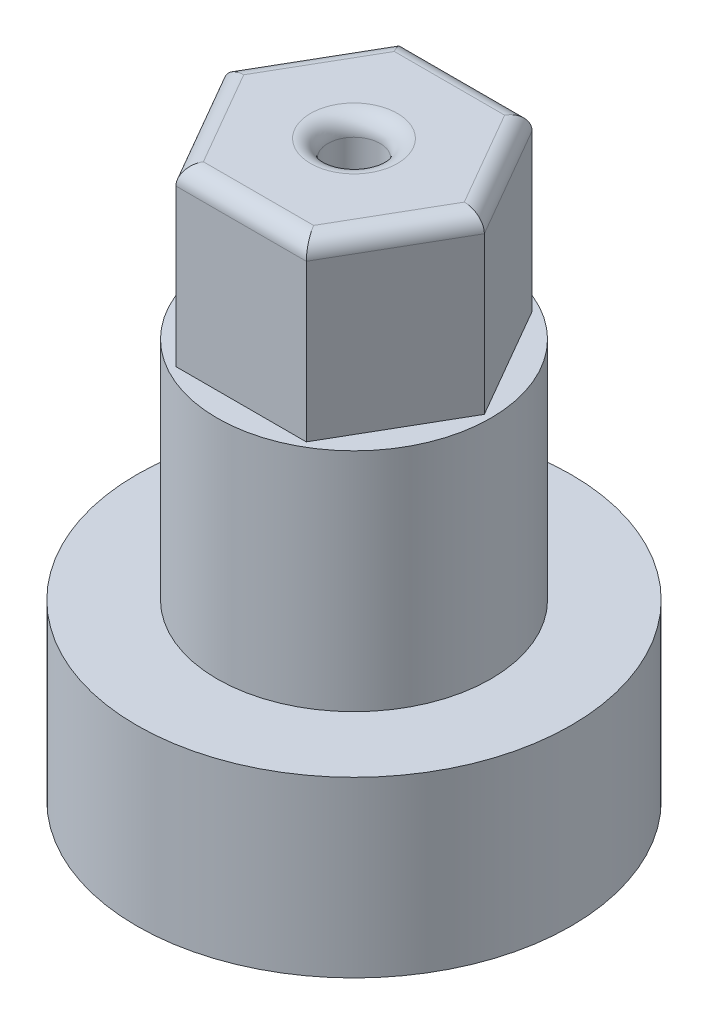
SolidWorks part; units mm, degrees
ref_plane "Alzado" through (0, 0, 0) normal (0, 0, 1) x (1, 0, 0)
ref_plane "Planta" through (0, 0, 0) normal (0, 1, 0) x (1, 0, 0)
ref_plane "Vista lateral" through (0, 0, 0) normal (1, 0, 0) x (0, 0, -1)
sketch "Croquis1" plane through (0, 0, 0) normal (0, 1, 0) x (1, 0, 0)
  line L0 (-12.5, 0) -> (12.5, 0) construction
  circle A0 centre (0, 0) radius 12.5
  circle A1 centre (7, 0) radius 0.75
  circle A2 centre (0, -7) radius 0.75
  circle A3 centre (-7, 0) radius 0.75
  circle A4 centre (0, 7) radius 0.75
  point P16 (0, 0)
  dimension "D1" = 25
  dimension "D2" = 1.5
  dimension "D3" = 7
  dimension "D4" = 4
extrude "Saliente-Extruir1" add sketch "Croquis1" along normal blind 10
sketch "Croquis2" plane through (0, 10, 0) normal (0, 1, 0) x (1, 0, 0)
  circle A0 centre (0, 0) radius 7.875
  dimension "D1" = 15.75
extrude "Saliente-Extruir2" add sketch "Croquis2" along normal blind 13
sketch "Croquis5" plane through (0, 10, 0) normal (0, 1, 0) x (1, 0, 0)
  circle A0 centre (0, 0) radius 12.5
sketch "Croquis3" plane through (0, 23, 0) normal (0, 1, 0) x (1, 0, 0)
  line L1 (7.5, 0) -> (3.75, 6.4952)
  line L2 (3.75, 6.4952) -> (-3.75, 6.4952)
  line L3 (-3.75, 6.4952) -> (-7.5, 0)
  line L4 (-7.5, 0) -> (-3.75, -6.4952)
  line L5 (-3.75, -6.4952) -> (3.75, -6.4952)
  line L6 (3.75, -6.4952) -> (7.5, 0)
  circle A0 centre (0, 0) radius 7.5 construction
extrude "Saliente-Extruir3" add sketch "Croquis3" along normal blind 10
sketch "Croquis4" plane through (0, 33, 0) normal (0, 1, 0) x (1, 0, 0)
  circle A0 centre (0, 0) radius 1.5
  dimension "D1" = 3
extrude "Cortar-Extruir1" cut sketch "Croquis4" against normal through all
fillet "Redondeo1" radius 1 7 edges at (0, 33, 6.4952) (-5.625, 33, 3.2476) (-5.625, 33, -3.2476) (0, 33, -6.4952) (5.625, 33, -3.2476) (5.625, 33, 3.2476) (0, 33, 1.5)
